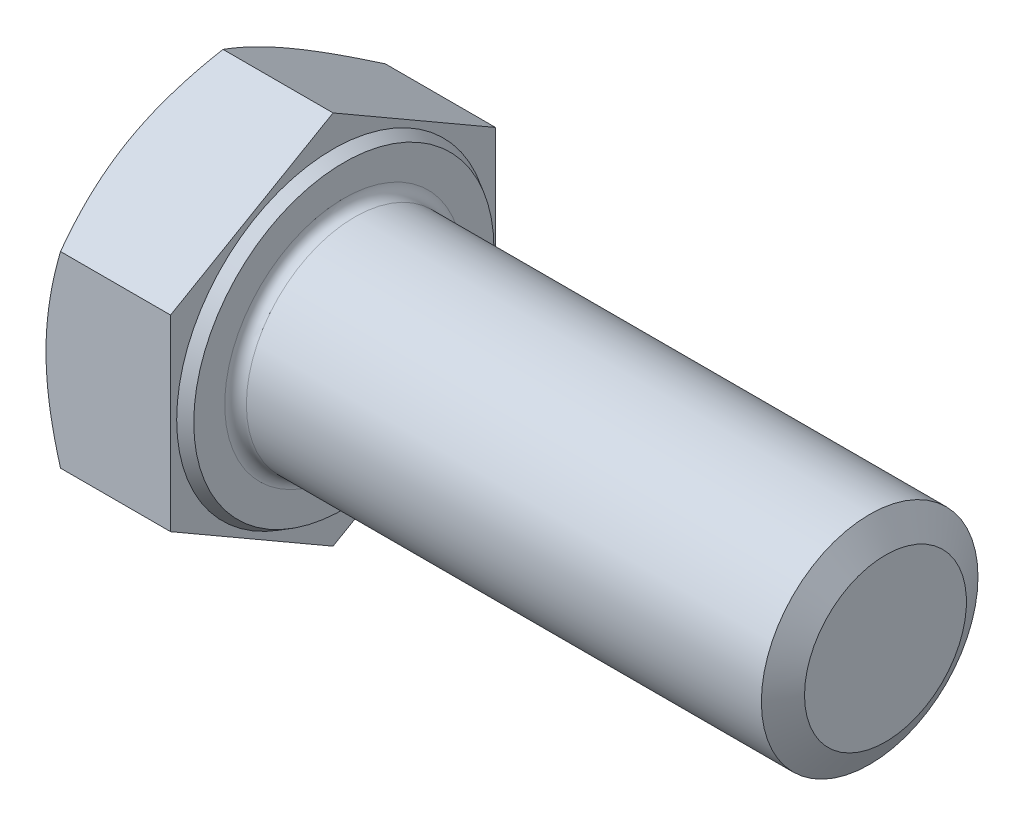
SolidWorks part; units mm, degrees
ref_plane "前视" through (0, 0, 0) normal (0, 0, 1) x (1, 0, 0)
ref_plane "上视" through (0, 0, 0) normal (0, 1, 0) x (1, 0, 0)
ref_plane "右视" through (0, 0, 0) normal (1, 0, 0) x (0, 0, -1)
sketch "草图1" plane through (0, 0, 0) normal (1, 0, 0) x (0, 0, -1)
  line L0 (9, 5.1962) -> (9, -5.1962)
  line L1 (-9, 5.1962) -> (-9, -5.1962)
  line L2 (9, -5.1962) -> (0, -10.3923)
  line L3 (0, -10.3923) -> (-9, -5.1962)
  line L4 (9, 5.1962) -> (0, 10.3923)
  line L5 (0, 10.3923) -> (-9, 5.1962)
  circle A0 centre (0, 0) radius 10.015 construction
  dimension "e" = 20.03
  dimension "s" = 18
  dimension "D2" = 120
  dimension "D3" = 9
  dimension "D4" = 9
  dimension "D5" = 9
extrude "基体-拉伸" add sketch "草图1" along normal blind 7.5
sketch "草图2" plane through (0, 0, 0) normal (0, 0, 1) x (1, 0, 0)
  line L0 (0, 5.1962) -> (0, -5.1962) construction
  line L1 (0, 0) -> (37.5, 0)
  line L2 (0, 0) -> (0, 6)
  line L3 (0, 6) -> (37.5, 6)
  line L4 (37.5, 0) -> (37.5, 4.4845)
  line L5 (7.5, 10.3923) -> (7.5, 5.1962) construction
  line L6 (0, 0) -> (-13.7, 0) construction
  line L7 (0, 0) -> (18.75, 0) construction
  line L8 (37.5, -4.4845) -> (90.335, -6) construction
  line L9 (0, -6) -> (90.335, -6) construction
  line L10 (9.25, 6) -> (9.25, 0) construction
  line L11 (7.5, 13.0554) -> (7.5, -1.27) construction
  line L12 (7.5, 5.1962) -> (7.5, -5.1962) construction
  line L14 (37.5, 6) -> (37.5, 4.4845)
  dimension "l" = 30
  dimension "d" = 12
  dimension "Minor_dia" = 8.969
  dimension "p" = 1.75
  dimension "b" = 30
  dimension "da" = 13.7
revolve "凸台-旋转1" add sketch "草图2" angle 360 about L7
cosmetic thread "螺旋线1" parameters "Thread_length"=27.375, "Thread_minor"=8.969
sketch "草图3" plane through (0, 0, 0) normal (0, 0, 1) x (1, 0, 0)
  line L0 (0, 9) -> (3.6906, 15.3923)
  line L1 (0, 10.3923) -> (0, 5.1962) construction
  line L2 (3.6906, 15.3923) -> (3.6906, 20.3923)
  line L3 (3.6906, 20.3923) -> (-10, 20.3923)
  line L4 (-10, 20.3923) -> (-10, 9)
  line L5 (-10, 9) -> (0, 9)
  line L6 (0, 0) -> (99.06, 0) construction
  line L7 (7.5, 10.3923) -> (0, 10.3923) construction
  dimension "D1" = 9
  dimension "D2" = 5
  dimension "D3" = 10
  dimension "D4" = 5
  dimension "Head_ch_ang" = 30
revolve "切除-旋转1" cut sketch "草图3" angle 360 about L6
sketch "草图4" plane through (0, 0, 0) normal (0, 0, 1) x (1, 0, 0)
  line L0 (0, 0) -> (248.9073, 0) construction
  line L2 (7.5, 0) -> (7.5, 8.315) construction
  line L3 (7.5, -6) -> (7.5, 6) construction
  line L4 (7.5, 10.3923) -> (7.5, 5.1962) construction
  line L9 (7.5, 8.315) -> (6.9, 8.6614)
  line L10 (6.9, 8.6614) -> (6.9, 10.3923)
  line L11 (7.5, 10.3923) -> (0.8038, 10.3923) construction
  line L12 (6.9, 10.3923) -> (7.5, 10.3923)
  line L13 (7.5, 10.3923) -> (7.5, 8.315)
  dimension "D1" = 120
  dimension "c" = 0.6
  dimension "dw" = 16.63
revolve "切除-旋转3" cut sketch "草图4" angle 360 about L0
fillet "圆角" radius 0.6 1 edges at (7.5, 0, -6)
sketch "草图6" plane through (0, 0, 0) normal (0, 0, 1) x (1, 0, 0)
  line L0 (0, 0) -> (37.5, 0) construction
  line L1 (37.5, -6) -> (37.5, 6) construction
  line L2 (37.5, 0) -> (37.5, 6) construction
  line L4 (36.625, 6) -> (38.375, 6)
  line L5 (36.625, 6) -> (37.5, 4.4845)
  line L6 (37.5, 4.4845) -> (38.375, 6)
  dimension "D1" = 1.75
revolve "切除-旋转4" cut sketch "草图6" angle 360 about L0
pattern_linear "阵列(线性)1" [suppressed]
